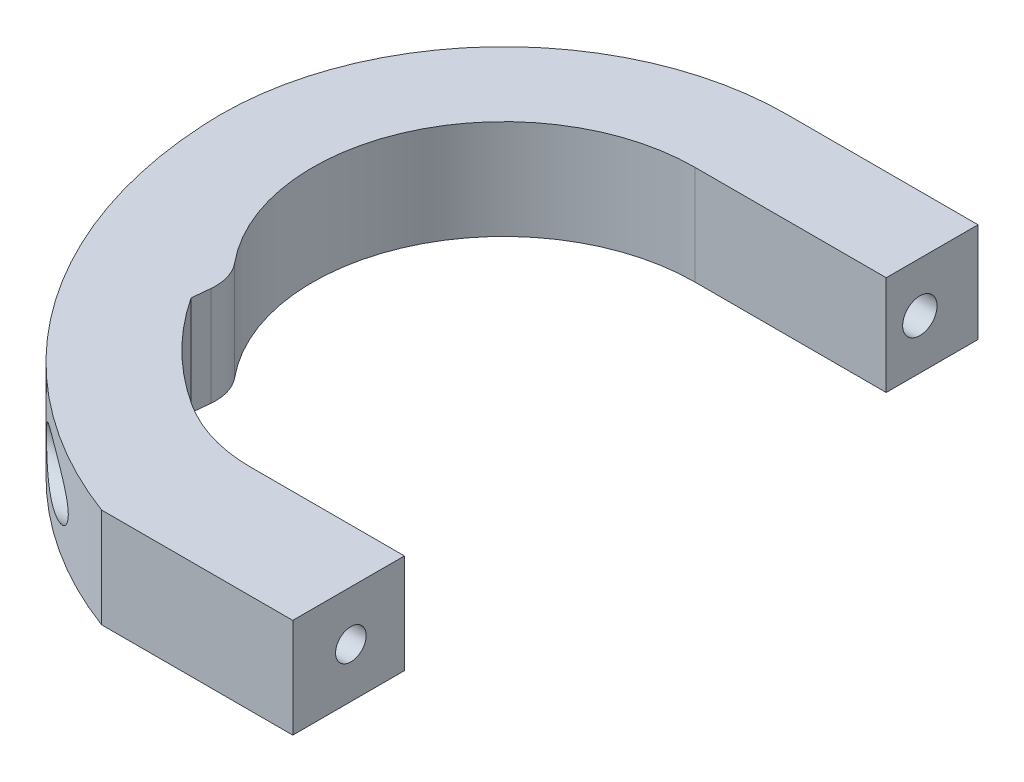
SolidWorks part; units mm, degrees
ref_plane "Front Plane" through (0, 0, 0) normal (0, 0, 1) x (1, 0, 0)
ref_plane "Top Plane" through (0, 0, 0) normal (0, 1, 0) x (1, 0, 0)
ref_plane "Right Plane" through (0, 0, 0) normal (1, 0, 0) x (0, 0, -1)
sketch "Sketch1" plane through (0, 0, 0) normal (0, 1, 0) x (1, 0, 0)
  circle A0 centre (0, 0) radius 12.5
  circle A1 centre (0, 0) radius 18.5
  dimension "D1" = 25
  dimension "D2" = 37
extrude "Boss-Extrude1" add sketch "Sketch1" along normal blind 6.5
sketch "Sketch2" plane through (0, 0, 0) normal (1, 0, 0) x (0, 0, -1)
  circle A0 centre (0, 0) radius 46.7029
extrude "Cut-Extrude1" cut sketch "Sketch2" along normal through all
sketch "Sketch3" plane through (0, 0, 0) normal (1, 0, 0) x (0, 0, -1)
  line L0 (18.5, 3.25) -> (14.7, 3.25)
  line L3 (18.5, 0) -> (18.5, 6.5) construction
  circle A0 centre (14.7, 3.25) radius 1.125
  dimension "D2" = 2.25
  dimension "D1" = 3.8
extrude "Cut-Extrude2" cut sketch "Sketch3" against normal through all and the other way through all contours A0
ref_plane "Plane1" through (-6.5, 0, 0) normal (1, 0, 0) x (0, 0, -1)
sketch "Sketch4" plane through (-6.5, 0, 0) normal (1, 0, 0) x (0, 0, -1)
  line L0 (0, 0) -> (14.7, 0)
  line L1 (14.7, 0) -> (14.7, 3.25)
  circle A0 centre (14.7, 3.25) radius 1.9
  dimension "D3" = 3.8
  dimension "D1" = 14.7
  dimension "D2" = 3.25
extrude "Cut-Extrude3" cut sketch "Sketch4" against normal through all contours A0
sketch "Sketch6" plane through (0, 0, 0) normal (1, 0, 0) x (0, 0, -1)
  line L1 (12.5, 6.5) -> (18.5, 6.5)
  line L2 (12.5, 6.5) -> (12.5, 0)
  line L3 (12.5, 0) -> (18.5, 0)
  line L4 (18.5, 6.5) -> (18.5, 0)
  circle A0 centre (14.7, 3.25) radius 1.125
extrude "Boss-Extrude2" add sketch "Sketch6" along normal blind 12.5
sketch "Sketch7" plane through (-6.5, 0, 0) normal (-1, 0, 0) x (0, 0, 1)
  circle A0 centre (-14.7, 3.25) radius 1.9
extrude "Cut-Extrude4" cut sketch "Sketch7" against normal blind 12.5
sketch "Sketch11" plane through (0, 0, 0) normal (0, 1, 0) x (1, 0, 0)
  line L0 (0, 0) -> (0, -18.5)
  line L1 (0, -18.5) -> (0, -26.3)
  arc A1 (0, 18.5) -> (0, -18.5) centre (0, 0) ccw construction
  arc A2 (0, -18.5) -> (-18.5, 0) centre (0.2286, 0.2286) cw
  arc A3 (0, -26.3) -> (-18.5, 0) centre (9.9378, 0.3471) cw
  dimension "D1" = 7.8
extrude "Boss-Extrude3" add sketch "Sketch11" along normal up to surface (6.5 mm away) contours L1 A2 A3 up to face at (-1, 6.5, -5.1667)
sketch "Sketch13" plane through (0, 0, 0) normal (0, -1, 0) x (-1, 0, 0)
  line L0 (0, -12.5) -> (0, -19)
  line L1 (0, -26.3) -> (0, -12.5) construction
  line L2 (9.0824, -11.3634) -> (8.8301, -8.8301)
  arc A0 (0, -12.5) -> (12.5, 0) centre (-0.0299, 0.0299) ccw
  arc A1 (0, -12.5) -> (0, 12.5) centre (0, 0) ccw construction
  arc A2 (0, -19) -> (12.5, 0) centre (-8.2653, 0.0496) ccw
  line M2 (0, -12.5) -> (0, -26.3)
  arc M9 (0, 12.5) -> (0, -12.5) centre (0, 0) cw
  dimension "D1" = 6.5
extrude "Cut-Extrude7" cut sketch "Sketch13" against normal blind 12.5 contours A2 L2 M2 M9
fillet "Fillet2" radius 3 1 edges at (-8.8317, 3.25, 8.846)
sketch "Sketch14" plane through (0, 0, 0) normal (1, 0, 0) x (0, 0, -1)
  line L0 (-26.3, 3.25) -> (-22.5, 3.25)
  line L1 (-26.3, 6.5) -> (-26.3, 0) construction
  circle A0 centre (-22.5, 3.25) radius 1
  dimension "D2" = 2
  dimension "D1" = 3.8
extrude "Cut-Extrude9" cut sketch "Sketch14" against normal through all contours A0
sketch "Sketch15" plane through (0, 0, 0) normal (1, 0, 0) x (0, 0, -1)
  line L1 (-26.3, 0) -> (-19, 0)
  line L2 (-26.3, 0) -> (-26.3, 6.5)
  line L3 (-26.3, 6.5) -> (-19, 6.5)
  line L4 (-19, 0) -> (-19, 6.5)
  circle A0 centre (-22.5, 3.25) radius 1
extrude "Boss-Extrude4" add sketch "Sketch15" along normal blind 12.5
fillet "Fillet3" radius 10 1 edges at (0, 3.25, 19)
ref_plane "Plane3" through (6, 0, 0) normal (1, 0, 0) x (0, 0, -1)
sketch "Sketch16" plane through (6, 0, 0) normal (1, 0, 0) x (0, 0, -1)
  line L0 (0, 0) -> (-22.5, 0)
  line L1 (-22.5, 0) -> (-22.5, 3.25)
  circle A1 centre (-22.5, 3.25) radius 1.9
  dimension "D2" = 3.25
  dimension "D3" = 3.8
  dimension "D1" = 22.5
extrude "Cut-Extrude11" cut sketch "Sketch16" against normal through all contours A1
